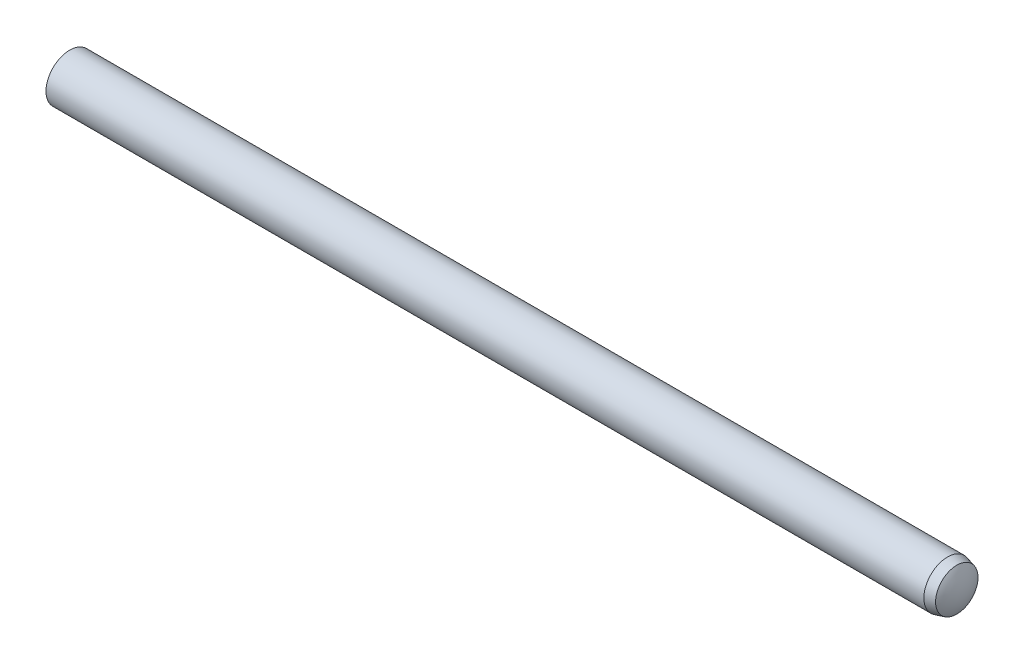
SolidWorks part; units mm, degrees
ref_plane "Front Plane" through (0, 0, 0) normal (0, 0, 1) x (1, 0, 0)
ref_plane "Top Plane" through (0, 0, 0) normal (0, 1, 0) x (1, 0, 0)
ref_plane "Right Plane" through (0, 0, 0) normal (1, 0, 0) x (0, 0, -1)
sketch "Sketch1" plane through (0, 0, 0) normal (0, 0, 1) x (1, 0, 0)
  line L0 (-19, 0) -> (19, 0) construction
  line L1 (19, 1) -> (19, -1) construction
  line L2 (-19, 1) -> (-19, -1) construction
  line L3 (18.35, 1) -> (18.35, -1) construction
  line L4 (-18.7, 1) -> (-18.7, -1) construction
  line L5 (-19, 0) -> (-18.7, 0) construction
  line L6 (19, 0) -> (18.35, 0) construction
  line L7 (18.74, 1) -> (18.74, -1) construction
  dimension "Dia" = 2
  dimension "Length" = 38
  dimension "D1" = 0.65
  dimension "D2" = 0.3
  dimension "D3" = 0.39
sketch "Sketch2" plane through (0, 0, 0) normal (1, 0, 0) x (0, 0, -1)
  circle A0 centre (0, 0) radius 1
extrude "Extrude1" add sketch "Sketch2" against normal up to vertex (19 mm away) and the other way up to vertex (19 mm away) up to point (-19, 0, 0) other way up to point (19, 0, 0)
sketch "Sketch5" plane through (0, 0, 0) normal (0, 0, 1) x (1, 0, 0)
  line L0 (18.35, 1) -> (18.35, 1.5)
  line L1 (18.35, 1.5) -> (19.5, 1.5)
  line L2 (19.5, 1.5) -> (19.5, 0)
  line L3 (19, 0) -> (19.5, 0)
  line L5 (-18.7, 1) -> (-18.7, 1.5)
  line L6 (-18.7, 1.5) -> (-19.5, 1.5)
  line L7 (-19.5, 1.5) -> (-19.5, 0)
  line L8 (18.35, 1) -> (18.74, 0.8955)
  line L10 (-19, 0) -> (-19.5, 0)
  line L11 (-19, 1) -> (-19, -1) construction
  line L13 (18.35, 1) -> (18.35, -1) construction
  line L15 (-19, 0) -> (19, 0) construction
  line L16 (18.74, 1) -> (18.74, -1) construction
  line L17 (19, 1) -> (19, -1) construction
  arc A0 (18.74, 0.8955) -> (19, 0) centre (17.3278, 0) cw
  arc A1 (-18.7, 1) -> (-19, 0) centre (-17.1833, 0) ccw
  dimension "D1" = 15
  dimension "D2" = 0.5
revolve "Cut-Revolve1" cut sketch "Sketch5" angle 360 about L0
equation "\"D1@Sketch1\" = \"Dia@Sketch1\"*.325"
equation "\"D2@Sketch1\" = \"Dia@Sketch1\"*.15"
equation "\"D3@Sketch1\" = \"D1@Sketch1\"*.6"
